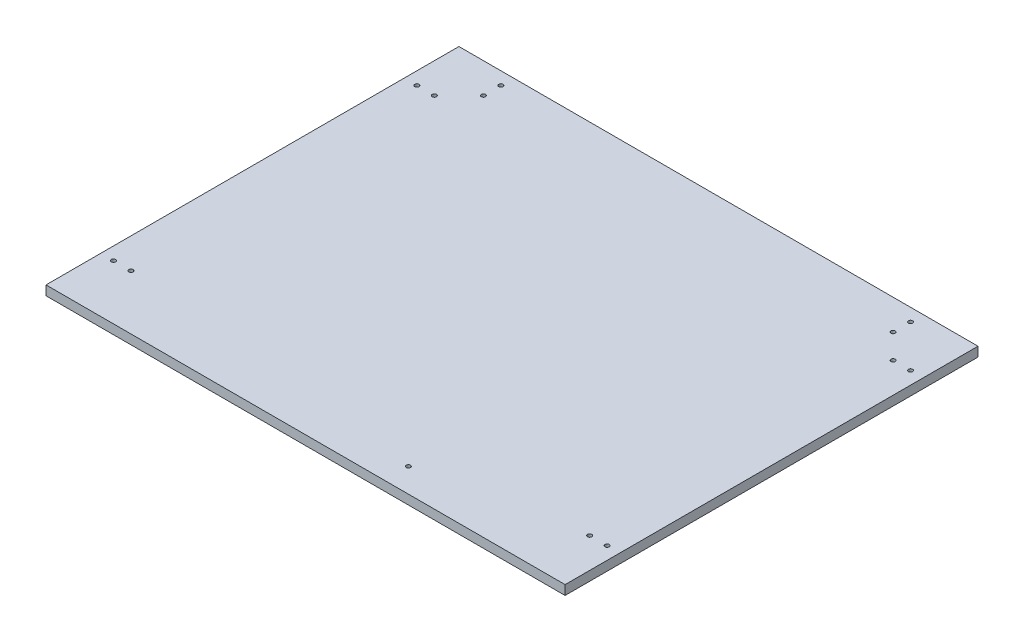
SolidWorks part; units mm, degrees
material "Multistrato di pioppo"
ref_plane "Piano frontale" through (0, 0, 0) normal (0, 0, 1) x (1, 0, 0)
ref_plane "Piano superiore" through (0, 0, 0) normal (0, 1, 0) x (1, 0, 0)
ref_plane "Piano destro" through (0, 0, 0) normal (1, 0, 0) x (0, 0, -1)
sketch "Schizzo1" plane through (0, 0, 0) normal (0, 1, 0) x (1, 0, 0)
  line L1 (-275, 218.75) -> (275, 218.75)
  line L2 (-275, 218.75) -> (-275, -218.75)
  line L3 (-275, -218.75) -> (275, -218.75)
  line L4 (275, 218.75) -> (275, -218.75)
  line L5 (-275, 218.75) -> (275, -218.75) construction
  line L6 (-275, -218.75) -> (275, 218.75) construction
  point P4 (0, 0)
  dimension "D1" = 550
  dimension "D2" = 437.5
extrude "Estrusione-Estrusione1" add sketch "Schizzo1" along normal blind 10
sketch "Schizzo2" plane through (0, 0, 0) normal (0, -1, 0) x (-1, 0, 0)
  circle A0 centre (-217, 205.25) radius 2.25
  circle A1 centre (-217, 186.75) radius 2.25
  circle A2 centre (-243, 160.75) radius 2.25
  circle A3 centre (-261.5, 160.75) radius 2.25
  circle A4 centre (217, 205.25) radius 2.25
  circle A5 centre (217, 186.75) radius 2.25
  circle A6 centre (243, 160.75) radius 2.25
  circle A7 centre (261.5, 160.75) radius 2.25
  circle A8 centre (261.5, -160.75) radius 2.25
  circle A9 centre (243, -160.75) radius 2.25
  circle A10 centre (-261.5, -160.75) radius 2.25
  circle A11 centre (-243, -160.75) radius 2.25
  circle A12 centre (-83.5, -193.25) radius 2.25
  point P39 (0, 0)
  point P40 (-83.5, -193.25)
  dimension "D1" = 4.5
extrude "Taglio-Estrusione1" cut sketch "Schizzo2" against normal blind 10
sketch "Schizzo3" plane through (0, 10, 0) normal (0, 1, 0) x (1, 0, 0)
  line L0 (-275, 0) -> (-259.6, 0)
  line L1 (-275, 218.75) -> (-275, -218.75) construction
  line L2 (-259.6, 0) -> (-267.1, 10)
  line L3 (-267.1, 10) -> (-227.1, 10)
  line L4 (-227.1, 10) -> (-234.6, 0)
  line L5 (-234.6, 0) -> (-219.2, 0)
  line L6 (-259.6, 0) -> (-234.6, 0) construction
  line L7 (-247.1, 0) -> (-247.1, 10) construction
  line L10 (-219.2, 0) -> (-204.6889, 0)
  line L11 (-204.6889, 0) -> (-212.1889, 10)
  line L12 (-212.1889, 10) -> (-172.1889, 10)
  line L13 (-172.1889, 10) -> (-179.6889, 0)
  line L14 (-179.6889, 0) -> (-165.1778, 0)
  line L15 (-204.6889, 0) -> (-179.6889, 0) construction
  line L16 (-192.1889, 0) -> (-192.1889, 10) construction
  line L17 (-165.1778, 0) -> (-149.7778, 0)
  line L18 (-149.7778, 0) -> (-157.2778, 10)
  line L19 (-157.2778, 10) -> (-117.2778, 10)
  line L20 (-117.2778, 10) -> (-124.7778, 0)
  line L21 (-124.7778, 0) -> (-110.2667, 0)
  line L22 (-149.7778, 0) -> (-124.7778, 0) construction
  line L23 (-137.2778, 0) -> (-137.2778, 10) construction
  line L24 (-110.2667, 0) -> (-94.8667, 0)
  line L25 (-94.8667, 0) -> (-102.3667, 10)
  line L26 (-102.3667, 10) -> (-62.3667, 10)
  line L27 (-62.3667, 10) -> (-69.8667, 0)
  line L28 (-69.8667, 0) -> (-55.3556, 0)
  line L29 (-94.8667, 0) -> (-69.8667, 0) construction
  line L30 (-82.3667, 0) -> (-82.3667, 10) construction
  line L31 (-55.3556, 0) -> (-39.9556, 0)
  line L32 (-39.9556, 0) -> (-47.4556, 10)
  line L33 (-47.4556, 10) -> (-7.4556, 10)
  line L34 (-7.4556, 10) -> (-14.9556, 0)
  line L35 (-14.9556, 0) -> (-0.4444, 0)
  line L36 (-39.9556, 0) -> (-14.9556, 0) construction
  line L37 (-27.4556, 0) -> (-27.4556, 10) construction
  line L38 (-0.4444, 0) -> (14.9556, 0)
  line L39 (14.9556, 0) -> (7.4556, 10)
  line L40 (7.4556, 10) -> (47.4556, 10)
  line L41 (47.4556, 10) -> (39.9556, 0)
  line L42 (39.9556, 0) -> (54.4667, 0)
  line L43 (14.9556, 0) -> (39.9556, 0) construction
  line L44 (27.4556, 0) -> (27.4556, 10) construction
  line L45 (54.4667, 0) -> (69.8667, 0)
  line L46 (69.8667, 0) -> (62.3667, 10)
  line L47 (62.3667, 10) -> (102.3667, 10)
  line L48 (102.3667, 10) -> (94.8667, 0)
  line L49 (94.8667, 0) -> (109.3778, 0)
  line L50 (69.8667, 0) -> (94.8667, 0) construction
  line L51 (82.3667, 0) -> (82.3667, 10) construction
  line L52 (109.3778, 0) -> (124.7778, 0)
  line L53 (124.7778, 0) -> (117.2778, 10)
  line L54 (117.2778, 10) -> (157.2778, 10)
  line L55 (157.2778, 10) -> (149.7778, 0)
  line L56 (149.7778, 0) -> (164.2889, 0)
  line L57 (124.7778, 0) -> (149.7778, 0) construction
  line L58 (137.2778, 0) -> (137.2778, 10) construction
  line L59 (164.2889, 0) -> (179.6889, 0)
  line L60 (179.6889, 0) -> (172.1889, 10)
  line L61 (172.1889, 10) -> (212.1889, 10)
  line L62 (212.1889, 10) -> (204.6889, 0)
  line L63 (204.6889, 0) -> (219.2, 0)
  line L64 (179.6889, 0) -> (204.6889, 0) construction
  line L65 (192.1889, 0) -> (192.1889, 10) construction
  line L66 (219.2, 0) -> (234.6, 0)
  line L67 (234.6, 0) -> (227.1, 10)
  line L68 (227.1, 10) -> (267.1, 10)
  line L69 (267.1, 10) -> (259.6, 0)
  line L70 (259.6, 0) -> (275, 0)
  line L71 (234.6, 0) -> (259.6, 0) construction
  line L72 (247.1, 0) -> (247.1, 10) construction
  line L73 (275, -218.75) -> (275, 218.75) construction
  dimension "D1" = 55.8
  dimension "D2" = 40
  dimension "D3" = 25
  dimension "D4" = 10
  dimension "D5" = 10
